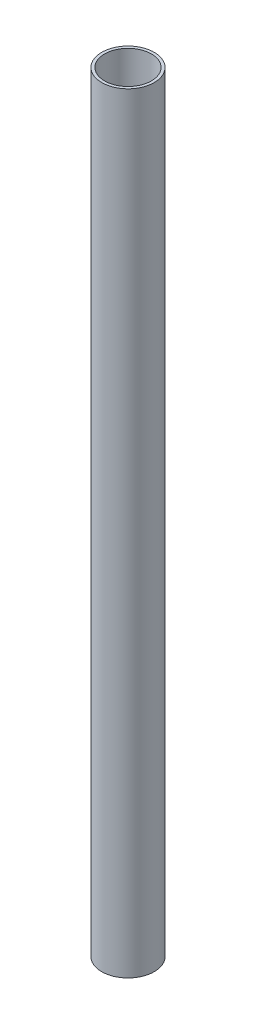
SolidWorks part; units mm, degrees
material "S-Glass Fiber"
ref_plane "Front Plane" through (0, 0, 0) normal (0, 0, 1) x (1, 0, 0)
ref_plane "Top Plane" through (0, 0, 0) normal (0, 1, 0) x (1, 0, 0)
ref_plane "Right Plane" through (0, 0, 0) normal (1, 0, 0) x (0, 0, -1)
sketch "Sketch1" plane through (0, 0, 0) normal (0, 1, 0) x (1, 0, 0)
  circle A0 centre (0, 0) radius 33.465
  circle A1 centre (0, 0) radius 37.465
  dimension "D2" = 74.93
  dimension "D1" = 4
extrude "Boss-Extrude1" add sketch "Sketch1" along normal blind 1100
equation "\"OD\"= 2.95"
equation "\"D2@Sketch1\"=\"OD\""
equation "\"wall thickness\"=0.15748"
equation "\"D1@Sketch1\"=\"wall thickness\""
equation "\"length\"= 43.30708661in"
equation "\"D1@Boss-Extrude1\"=\"length\""
